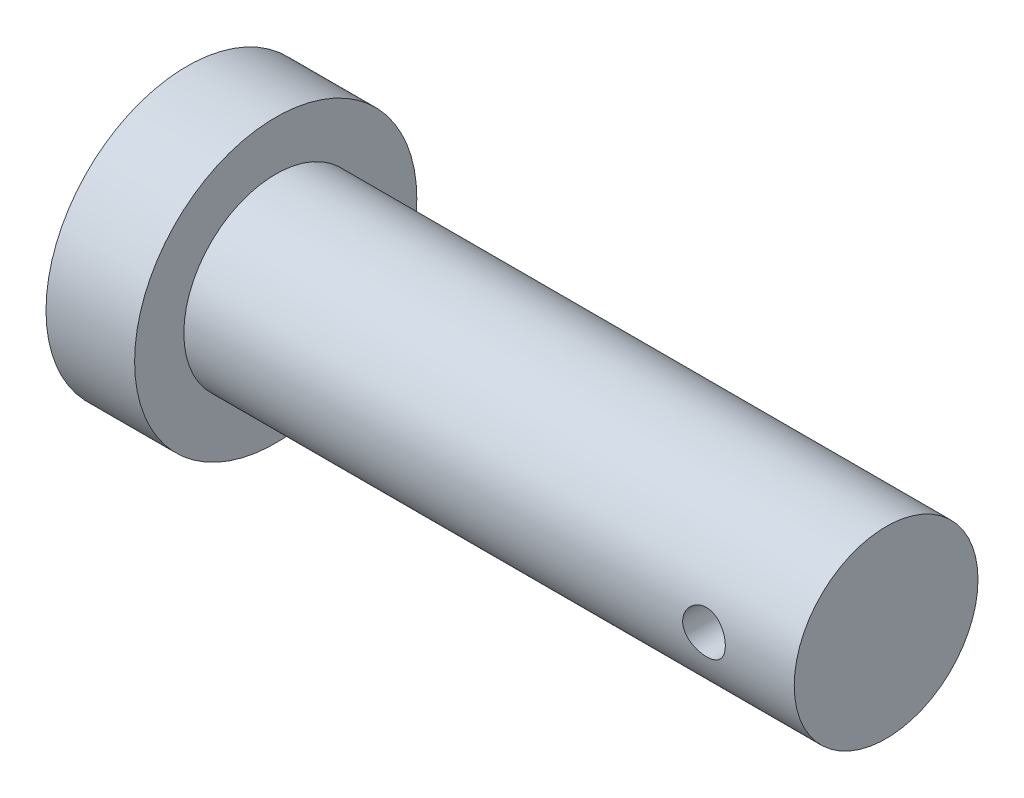
SolidWorks part; units mm, degrees
ref_plane "Front Plane" through (0, 0, 0) normal (0, 0, 1) x (1, 0, 0)
ref_plane "Top Plane" through (0, 0, 0) normal (0, 1, 0) x (1, 0, 0)
ref_plane "Right Plane" through (0, 0, 0) normal (1, 0, 0) x (0, 0, -1)
sketch "Sketch2" plane through (0, 0, 0) normal (0, 0, 1) x (1, 0, 0)
  line L0 (0, 0) -> (0, 39140.3095) construction
  line L1 (0, 0) -> (39140.3095, 0) construction
  line L2 (0, 0) -> (0, 43)
  line L3 (0, 43) -> (27, 43)
  line L4 (27, 43) -> (27, 28)
  line L5 (27, 28) -> (213, 28)
  line L6 (213, 28) -> (213, 0)
  line L7 (213, 0) -> (0, 0)
  dimension "D1" = 43
  dimension "D2" = 27
  dimension "D3" = 15
  dimension "D4" = 186
revolve "Revolve1" add sketch "Sketch2" angle 360 about L1
sketch "Sketch3" plane through (0, 0, 0) normal (0, 0, 1) x (1, 0, 0)
  line L0 (0, 0) -> (-50000, 0) construction
  line L1 (213, -28) -> (213, 28) construction
  circle A0 centre (185.5, 0) radius 6.5
  dimension "D1" = 27.5
  dimension "D2" = 13
extrude "Cut-Extrude1" cut sketch "Sketch3" against normal mid plane 80
